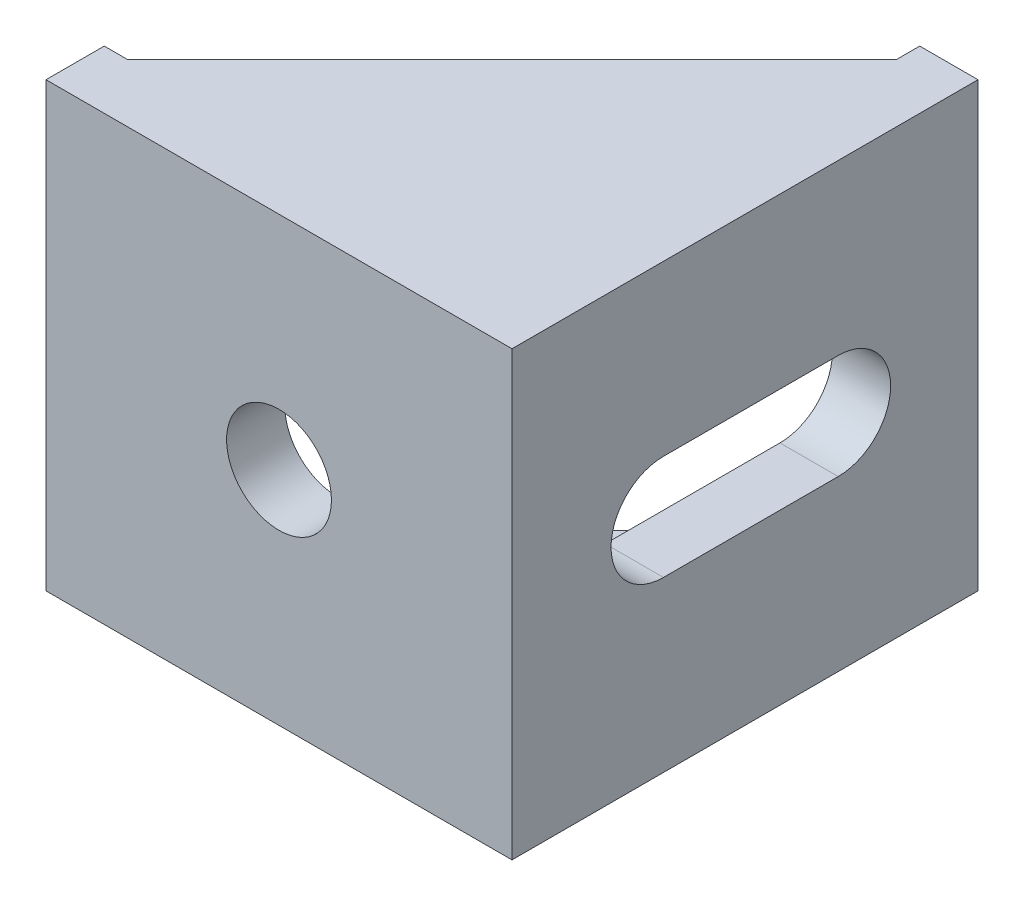
SolidWorks part; units mm, degrees
ref_plane "Front Plane" through (0, 0, 0) normal (0, 0, 1) x (1, 0, 0)
ref_plane "Top Plane" through (0, 0, 0) normal (0, 1, 0) x (1, 0, 0)
ref_plane "Right Plane" through (0, 0, 0) normal (1, 0, 0) x (0, 0, -1)
sketch "Sketch1" plane through (0, 0, 0) normal (0, 1, 0) x (1, 0, 0)
  line L0 (0, 0) -> (0, 40)
  line L1 (0, 0) -> (-40, 0)
  dimension "D1" = 40
  dimension "D2" = 40
extrude "Extrude-Thin1" add sketch "Sketch1" along normal mid plane 38 thin thin type one direction wall 5
sketch "Sketch2" plane through (0, 0, 0) normal (1, 0, 0) x (0, 0, -1)
  line L0 (0, 0) -> (49.2887, 0) construction
  line L1 (13, 0) -> (28, 0) construction
  line L2 (13, 4.5) -> (28, 4.5)
  line L3 (13, -4.5) -> (28, -4.5)
  line L4 (0, 19) -> (0, -19) construction
  arc A0 (13, 4.5) -> (13, -4.5) centre (13, 0) ccw
  arc A1 (28, -4.5) -> (28, 4.5) centre (28, 0) ccw
  point P5 (20.5, 0)
  dimension "D1" = 13
  dimension "D2" = 9
  dimension "D3" = 15
extrude "Cut-Extrude1" cut sketch "Sketch2" against normal through all
sketch "Sketch3" plane through (0, 0, 0) normal (0, 0, 1) x (1, 0, 0)
  line L0 (0, 0) -> (-46.0229, 0) construction
  line L1 (0, 19) -> (0, -19) construction
  circle A0 centre (-20, 0) radius 4.5
  dimension "D2" = 9
  dimension "D1" = 20
extrude "Cut-Extrude2" cut sketch "Sketch3" against normal through all
sketch "Sketch4" plane through (0, 19, 0) normal (0, 1, 0) x (1, 0, 0)
  line L0 (-38, 5) -> (-5, 38)
  line L1 (-5, 5) -> (-40, 5) construction
  line L2 (-5, 40) -> (-5, 5) construction
  line L3 (0, 40) -> (0, 0) construction
  line L4 (0, 0) -> (-40, 0) construction
  line L5 (-38, 5) -> (-5, 5)
  line L6 (-5, 5) -> (-5, 38)
  dimension "D1" = 38
  dimension "D2" = 38
extrude "Boss-Extrude1" add sketch "Sketch4" against normal blind 3
mirror "Mirror1" about plane through (0, 0, 0) normal (0, 1, 0) of "Boss-Extrude1"
